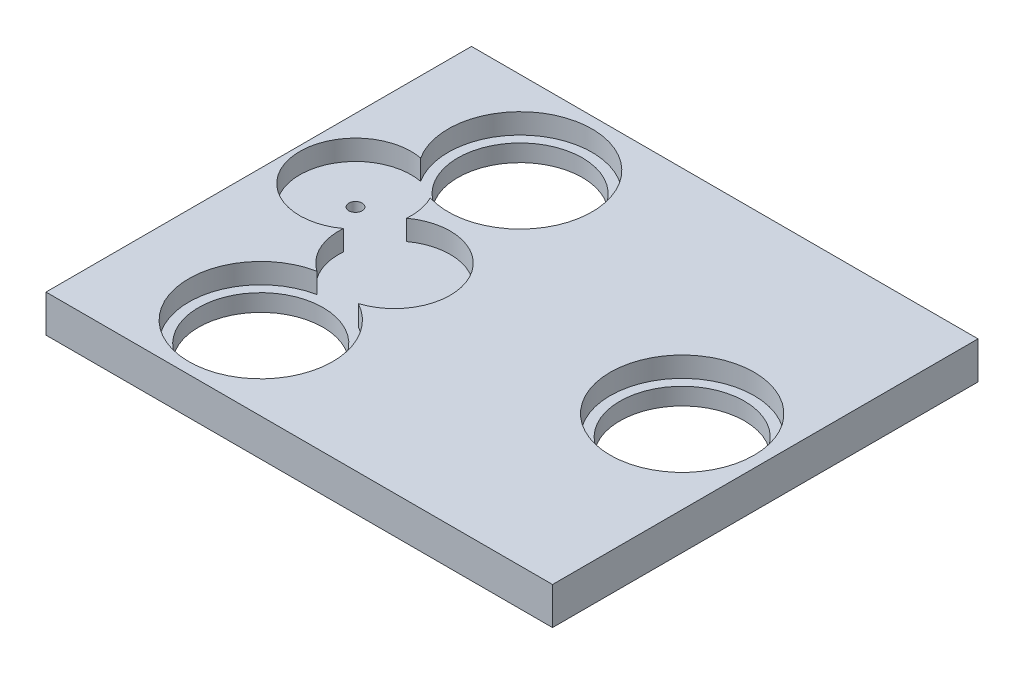
SolidWorks part; units mm, degrees
ref_plane "Front" through (0, 0, 0) normal (0, 0, 1) x (1, 0, 0)
ref_plane "Top" through (0, 0, 0) normal (0, 1, 0) x (1, 0, 0)
ref_plane "Right" through (0, 0, 0) normal (1, 0, 0) x (0, 0, -1)
sketch "Sketch1" plane through (0, 0, 0) normal (0, 1, 0) x (1, 0, 0)
  line L1 (-62.5, -52.5) -> (62.5, -52.5)
  line L2 (-62.5, -52.5) -> (-62.5, 52.5)
  line L3 (-62.5, 52.5) -> (62.5, 52.5)
  line L4 (62.5, -52.5) -> (62.5, 52.5)
  line L5 (-62.5, -52.5) -> (62.5, 52.5) construction
  line L6 (-62.5, 52.5) -> (62.5, -52.5) construction
  point P0 (0, 0)
  dimension "D1" = 125
  dimension "D2" = 105
extrude "Test_Base_Postion" add sketch "Sketch1" along normal blind 9.215
sketch "Thumb_Position" plane through (0, 9.215, 0) normal (0, 1, 0) x (1, 0, 0)
  line L0 (62.5, -52.5) -> (62.5, 52.5) construction
  line L1 (49, -12) -> (17, -12)
  line L2 (49, -12) -> (49, 43)
  line L3 (49, 43) -> (17, 43)
  line L4 (17, -12) -> (17, 43)
  line L5 (33, 43) -> (33, -12) construction
  line L6 (51, -12) -> (15, -12)
  line L7 (51, -12) -> (51, 12)
  line L8 (51, 12) -> (15, 12)
  line L9 (15, -12) -> (15, 12)
  line L10 (33, 12) -> (33, -12) construction
  line L12 (51, 0) -> (15, 0) construction
  circle A1 centre (42, 0) radius 9
  circle A2 centre (42, 0) radius 17.75 construction
  dimension "D6" = 18
  dimension "D7" = 20.5
  dimension "D5" = 35.5
  dimension "D1" = 55
  dimension "D2" = 32
  dimension "D3" = 36
  dimension "D4" = 24
sketch "Finger_Gears_Position" plane through (0, 0, 0) normal (0, -1, 0) x (1, 0, 0)
  line L0 (-30, 32) -> (-30, 49.5) construction
  line L1 (-30, 32) -> (-47.5, 32) construction
  line L2 (-30, -32) -> (-30, -49.5) construction
  line L3 (-30, -32) -> (-47.5, -32) construction
  line L4 (-62.5, -52.5) -> (-62.5, 52.5) construction
  line L5 (-62.5, 52.5) -> (62.5, 52.5) construction
  line L8 (62.5, -52.5) -> (-62.5, -52.5) construction
  line L9 (-62.5, 0) -> (62.5, 0) construction
  line L10 (62.5, 52.5) -> (62.5, -52.5) construction
  line L13 (-30, -32) -> (-43, -32) construction
  line L15 (-43, -48) -> (12, -48) construction
  line L16 (-43, -48) -> (-43, -16) construction
  line L17 (-43, -16) -> (12, -16) construction
  line L18 (12, -48) -> (12, -16) construction
  line L20 (-30, 32) -> (-43, 32) construction
  line L21 (12, -32) -> (-23, -32) construction
  line L22 (-43, 16) -> (12, 16) construction
  line L23 (-43, 16) -> (-43, 48) construction
  line L24 (-43, 48) -> (12, 48) construction
  line L25 (12, 16) -> (12, 48) construction
  line L26 (12, 32) -> (-23, 32) construction
  line L27 (-23, -32) -> (-23, 32) construction
  circle A0 centre (-30, 32) radius 17.5 construction
  circle A1 centre (-30, -32) radius 17.5 construction
  dimension "D1" = 35
  dimension "D2" = 15
  dimension "D3" = 3
  dimension "D4" = 3
  dimension "D5" = 13
  dimension "D6" = 55
  dimension "D7" = 32
  dimension "D8" = 13
  dimension "D9" = 55
  dimension "D10" = 32
  dimension "D11" = 35
  dimension "D12" = 35
sketch "Fingers_Position" plane through (0, 9.215, 0) normal (0, 1, 0) x (1, 0, 0)
  line L0 (12, 32) -> (-23, 32) construction
  line L1 (12, 16) -> (-43, 16)
  line L2 (12, 16) -> (12, 48)
  line L3 (12, 48) -> (-43, 48)
  line L4 (-43, 16) -> (-43, 48)
  line L5 (12, -48) -> (-43, -48)
  line L6 (12, -48) -> (12, -16)
  line L7 (12, -16) -> (-43, -16)
  line L8 (-43, -48) -> (-43, -16)
  line L9 (-23, 32) -> (-23, -32) construction
  line L10 (-23, -32) -> (12, -32) construction
sketch "Thumb_Knuckle_Mount_Position" plane through (0, 0, 0) normal (0, -1, 0) x (1, 0, 0)
  circle A0 centre (42, 0) radius 17.75
  dimension "D1" = 35.5
sketch "Gears_Position" plane through (0, 0, 0) normal (0, -1, 0) x (-1, 0, 0)
  line L0 (30, 32) -> (30, 13.5) construction
  line L1 (30, 32) -> (30.5905, 16.5113) construction
  line L2 (30.7851, 15.5187) -> (29.2149, 15.5187) construction
  line L3 (31.4977, 13.5607) -> (30, 17.6757) construction
  line L4 (28.2415, 13.5838) -> (30, 32) construction
  line L5 (29.2149, 15.5187) -> (27.6518, 15.6679) construction
  line L6 (30, -32) -> (30, -50.5) construction
  line L7 (30.7851, -48.4813) -> (29.2149, -48.4813) construction
  line L8 (30.5905, -47.4887) -> (30, -32) construction
  line L9 (31.4977, -50.4393) -> (30, -46.3243) construction
  line L10 (30, -32) -> (28.2415, -50.4162) construction
  line L11 (29.2149, -48.4813) -> (27.6518, -48.3321) construction
  line L12 (47.5, 8.8753) -> (47.5, -5.6247) construction
  line L13 (47.5, 8.8753) -> (48.0842, -2.6098) construction
  line L14 (48.2849, -3.6) -> (46.7151, -3.6) construction
  line L15 (48.9937, -5.5475) -> (47.5, -1.4436) construction
  line L16 (47.5, 8.8753) -> (45.6827, -5.5103) construction
  line L17 (46.7151, -3.6) -> (45.1577, -3.4033) construction
  line L18 (26.4633, -15.7991) -> (24.8935, -15.7991) construction
  line L19 (25.6784, -3.3238) -> (23.8611, -17.7095) construction
  line L20 (24.8935, -15.7991) -> (23.3362, -15.6024) construction
  line L21 (25.6784, -3.3238) -> (25.6784, -17.8238) construction
  line L22 (25.6784, -3.3238) -> (26.2626, -14.809) construction
  line L23 (27.1722, -17.7467) -> (25.6784, -13.6427) construction
  line L24 (-0.062, 11.1823) -> (33.5, -16.1231) construction
  line L25 (35.7758, 7.7687) -> (-2.3378, -12.7095) construction
  line L26 (-0.062, 11.1823) -> (35.7758, 7.7687) construction
  line L27 (-0.062, 11.1823) -> (-2.3378, -12.7095) construction
  line L28 (-2.3378, -12.7095) -> (33.5, -16.1231) construction
  line L29 (35.7758, 7.7687) -> (33.5, -16.1231) construction
  line L30 (16.719, -2.4704) -> (34.6379, -4.1772) construction
  line L31 (62.5, 52.5) -> (62.5, -52.5) construction
  circle A0 centre (30, -32) radius 17.5 construction
  circle A1 centre (30, 32) radius 17.5 construction
  circle A2 centre (30, 32) radius 16.5
  circle A3 centre (30, 32) radius 15.5 construction
  circle A4 centre (30, 32) radius 18.5 construction
  arc A5 (32.4899, 13.6683) -> (30.5905, 16.5113) centre (33.854, 16.6357) cw
  arc A6 (27.5101, 13.6683) -> (29.4095, 16.5113) centre (26.146, 16.6357) ccw
  arc A7 (32.4899, -50.3317) -> (30.5905, -47.4887) centre (33.854, -47.3643) cw
  arc A8 (27.5101, -50.3317) -> (29.4095, -47.4887) centre (26.146, -47.3643) ccw
  circle A9 centre (30, -32) radius 16.5
  circle A10 centre (30, -32) radius 18.5 construction
  circle A11 centre (30, -32) radius 15.5 construction
  arc A12 (28.9757, -50.4716) -> (27.6486, -47.3206) centre (30.8766, -47.816) cw
  arc A13 (24.0858, -49.5292) -> (26.4889, -47.0971) centre (23.3079, -46.3573) ccw
  arc A14 (25.4984, -49.944) -> (24.7916, -46.5987) centre (27.8676, -47.6961) cw
  arc A15 (20.8752, -48.0931) -> (23.6952, -46.1598) centre (20.7117, -44.8314) ccw
  arc A16 (22.1838, -48.7678) -> (22.1229, -45.3492) centre (24.9356, -47.0089) cw
  arc A17 (17.9945, -46.0754) -> (21.1294, -44.7107) centre (18.4512, -42.8417) ccw
  arc A18 (19.1518, -46.9855) -> (19.7389, -43.6172) centre (22.1867, -45.7792) cw
  arc A19 (15.5476, -43.549) -> (18.8842, -42.8022) centre (16.6081, -40.4601) ccw
  arc A20 (16.5118, -44.6617) -> (17.7258, -41.4654) centre (19.7201, -44.0516) cw
  arc A21 (13.6232, -40.6052) -> (17.0407, -40.5033) centre (15.2491, -37.7728) ccw
  arc A22 (14.3593, -41.8802) -> (16.1562, -38.9714) centre (17.6251, -41.8883) cw
  arc A23 (12.2906, -37.3503) -> (15.6656, -37.8971) centre (14.4231, -34.8769) ccw
  arc A24 (12.7721, -38.7416) -> (15.0871, -36.2255) centre (15.9774, -39.3676) cw
  arc A25 (11.598, -33.9021) -> (14.8086, -35.0777) centre (14.1602, -31.8769) ccw
  arc A26 (11.8076, -35.3594) -> (14.5569, -33.3268) centre (14.8365, -36.5807) cw
  arc A27 (11.5706, -30.3851) -> (14.5007, -32.1471) centre (14.4697, -28.8814) ccw
  arc A28 (11.5006, -31.8557) -> (14.5849, -30.3802) centre (14.2436, -33.6282) cw
  arc A29 (12.2093, -26.9265) -> (14.7529, -29.2112) centre (15.3405, -25.9987) ccw
  arc A30 (11.8622, -28.3573) -> (15.17, -27.4922) centre (14.2202, -30.6169) cw
  arc A31 (13.4909, -23.6513) -> (15.5563, -26.3761) centre (16.7412, -23.3328) ccw
  arc A32 (12.8793, -24.9905) -> (16.2911, -24.767) centre (14.7671, -27.6555) cw
  arc A33 (15.3693, -20.6778) -> (16.8816, -23.7442) centre (18.6211, -20.9802) ccw
  arc A34 (14.5153, -21.8771) -> (17.9077, -22.3033) centre (15.8646, -24.8512) cw
  arc A35 (17.7764, -18.1135) -> (18.6811, -21.4107) centre (20.9122, -19.0259) ccw
  arc A36 (16.7109, -19.1295) -> (19.9613, -20.1901) centre (17.473, -22.3052) cw
  arc A37 (20.6253, -16.0511) -> (20.8897, -19.46) centre (23.5318, -17.5404) ccw
  arc A38 (19.3868, -16.8471) -> (22.3778, -18.5036) centre (19.5341, -20.1096) cw
  arc A39 (23.8131, -14.5652) -> (23.4275, -17.9625) centre (26.3852, -16.5776) ccw
  arc A40 (22.4463, -15.1124) -> (25.0697, -17.305) centre (21.9735, -18.3438) cw
  arc A41 (27.2245, -13.7094) -> (26.2029, -16.9723) centre (29.3693, -16.1722) ccw
  arc A42 (25.7788, -13.988) -> (27.9399, -16.6375) centre (24.703, -17.0716) cw
  arc A43 (30.7361, -13.5147) -> (29.1155, -16.5253) centre (32.3761, -16.3389) ccw
  arc A44 (29.2639, -13.5147) -> (30.8845, -16.5253) centre (27.6239, -16.3389) cw
  arc A45 (34.2212, -13.988) -> (32.0601, -16.6375) centre (35.297, -17.0716) ccw
  arc A46 (32.7755, -13.7094) -> (33.7971, -16.9723) centre (30.6307, -16.1722) cw
  arc A47 (37.5537, -15.1124) -> (34.9303, -17.305) centre (38.0265, -18.3438) ccw
  arc A48 (36.1869, -14.5652) -> (36.5725, -17.9625) centre (33.6148, -16.5776) cw
  arc A49 (40.6132, -16.8471) -> (37.6222, -18.5036) centre (40.4659, -20.1096) ccw
  arc A50 (39.3747, -16.0511) -> (39.1103, -19.46) centre (36.4682, -17.5404) cw
  arc A51 (43.2891, -19.1295) -> (40.0387, -20.1901) centre (42.527, -22.3052) ccw
  arc A52 (42.2236, -18.1135) -> (41.3189, -21.4107) centre (39.0878, -19.0259) cw
  arc A53 (45.4847, -21.8771) -> (42.0923, -22.3033) centre (44.1354, -24.8512) ccw
  arc A54 (44.6307, -20.6778) -> (43.1184, -23.7442) centre (41.3789, -20.9802) cw
  arc A55 (47.1207, -24.9905) -> (43.7089, -24.767) centre (45.2329, -27.6555) ccw
  arc A56 (46.5091, -23.6513) -> (44.4437, -26.3761) centre (43.2588, -23.3328) cw
  arc A57 (48.1378, -28.3573) -> (44.83, -27.4922) centre (45.7798, -30.6169) ccw
  arc A58 (47.7907, -26.9265) -> (45.2471, -29.2112) centre (44.6595, -25.9987) cw
  arc A59 (48.4994, -31.8557) -> (45.4151, -30.3802) centre (45.7564, -33.6282) ccw
  arc A60 (48.4294, -30.3851) -> (45.4993, -32.1471) centre (45.5303, -28.8814) cw
  arc A61 (48.1924, -35.3594) -> (45.4431, -33.3268) centre (45.1635, -36.5807) ccw
  arc A62 (48.402, -33.9021) -> (45.1914, -35.0777) centre (45.8398, -31.8769) cw
  arc A63 (47.2279, -38.7416) -> (44.9129, -36.2255) centre (44.0226, -39.3676) ccw
  arc A64 (47.7094, -37.3503) -> (44.3344, -37.8971) centre (45.5769, -34.8769) cw
  arc A65 (45.6407, -41.8802) -> (43.8438, -38.9714) centre (42.3749, -41.8883) ccw
  arc A66 (46.3768, -40.6052) -> (42.9593, -40.5033) centre (44.7509, -37.7728) cw
  arc A67 (43.4882, -44.6617) -> (42.2742, -41.4654) centre (40.2799, -44.0516) ccw
  arc A68 (44.4524, -43.549) -> (41.1158, -42.8022) centre (43.3919, -40.4601) cw
  arc A69 (40.8482, -46.9855) -> (40.2611, -43.6172) centre (37.8133, -45.7792) ccw
  arc A70 (42.0055, -46.0754) -> (38.8706, -44.7107) centre (41.5488, -42.8417) cw
  arc A71 (37.8162, -48.7678) -> (37.8771, -45.3492) centre (35.0644, -47.0089) ccw
  arc A72 (39.1248, -48.0931) -> (36.3048, -46.1598) centre (39.2883, -44.8314) cw
  arc A73 (34.5016, -49.944) -> (35.2084, -46.5987) centre (32.1324, -47.6961) ccw
  arc A74 (35.9142, -49.5292) -> (33.5111, -47.0971) centre (36.6921, -46.3573) cw
  arc A75 (31.0243, -50.4716) -> (32.3514, -47.3206) centre (29.1234, -47.816) ccw
  arc A76 (28.9757, 13.5284) -> (27.6486, 16.6794) centre (30.8766, 16.184) cw
  arc A77 (24.0858, 14.4708) -> (26.4889, 16.9029) centre (23.3079, 17.6427) ccw
  arc A78 (25.4984, 14.056) -> (24.7916, 17.4013) centre (27.8676, 16.3039) cw
  arc A79 (20.8752, 15.9069) -> (23.6952, 17.8402) centre (20.7117, 19.1686) ccw
  arc A80 (22.1838, 15.2322) -> (22.1229, 18.6508) centre (24.9356, 16.9911) cw
  arc A81 (17.9945, 17.9246) -> (21.1294, 19.2893) centre (18.4512, 21.1583) ccw
  arc A82 (19.1518, 17.0145) -> (19.7389, 20.3828) centre (22.1867, 18.2208) cw
  arc A83 (15.5476, 20.451) -> (18.8842, 21.1978) centre (16.6081, 23.5399) ccw
  arc A84 (16.5118, 19.3383) -> (17.7258, 22.5346) centre (19.7201, 19.9484) cw
  arc A85 (13.6232, 23.3948) -> (17.0407, 23.4967) centre (15.2491, 26.2272) ccw
  arc A86 (14.3593, 22.1198) -> (16.1562, 25.0286) centre (17.6251, 22.1117) cw
  arc A87 (12.2906, 26.6497) -> (15.6656, 26.1029) centre (14.4231, 29.1231) ccw
  arc A88 (12.7721, 25.2584) -> (15.0871, 27.7745) centre (15.9774, 24.6324) cw
  arc A89 (11.598, 30.0979) -> (14.8086, 28.9223) centre (14.1602, 32.1231) ccw
  arc A90 (11.8076, 28.6406) -> (14.5569, 30.6732) centre (14.8365, 27.4193) cw
  arc A91 (11.5706, 33.6149) -> (14.5007, 31.8529) centre (14.4697, 35.1186) ccw
  arc A92 (11.5006, 32.1443) -> (14.5849, 33.6198) centre (14.2436, 30.3718) cw
  arc A93 (12.2093, 37.0735) -> (14.7529, 34.7888) centre (15.3405, 38.0013) ccw
  arc A94 (11.8622, 35.6427) -> (15.17, 36.5078) centre (14.2202, 33.3831) cw
  arc A95 (13.4909, 40.3487) -> (15.5563, 37.6239) centre (16.7412, 40.6672) ccw
  arc A96 (12.8793, 39.0095) -> (16.2911, 39.233) centre (14.7671, 36.3445) cw
  arc A97 (15.3693, 43.3222) -> (16.8816, 40.2558) centre (18.6211, 43.0198) ccw
  arc A98 (14.5153, 42.1229) -> (17.9077, 41.6967) centre (15.8646, 39.1488) cw
  arc A99 (17.7764, 45.8865) -> (18.6811, 42.5893) centre (20.9122, 44.9741) ccw
  arc A100 (16.7109, 44.8705) -> (19.9613, 43.8099) centre (17.473, 41.6948) cw
  arc A101 (20.6253, 47.9489) -> (20.8897, 44.54) centre (23.5318, 46.4596) ccw
  arc A102 (19.3868, 47.1529) -> (22.3778, 45.4964) centre (19.5341, 43.8904) cw
  arc A103 (23.8131, 49.4348) -> (23.4275, 46.0375) centre (26.3852, 47.4224) ccw
  arc A104 (22.4463, 48.8876) -> (25.0697, 46.695) centre (21.9735, 45.6562) cw
  arc A105 (27.2245, 50.2906) -> (26.2029, 47.0277) centre (29.3693, 47.8278) ccw
  arc A106 (25.7788, 50.012) -> (27.9399, 47.3625) centre (24.703, 46.9284) cw
  arc A107 (30.7361, 50.4853) -> (29.1155, 47.4747) centre (32.3761, 47.6611) ccw
  arc A108 (29.2639, 50.4853) -> (30.8845, 47.4747) centre (27.6239, 47.6611) cw
  arc A109 (34.2212, 50.012) -> (32.0601, 47.3625) centre (35.297, 46.9284) ccw
  arc A110 (32.7755, 50.2906) -> (33.7971, 47.0277) centre (30.6307, 47.8278) cw
  arc A111 (37.5537, 48.8876) -> (34.9303, 46.695) centre (38.0265, 45.6562) ccw
  arc A112 (36.1869, 49.4348) -> (36.5725, 46.0375) centre (33.6148, 47.4224) cw
  arc A113 (40.6132, 47.1529) -> (37.6222, 45.4964) centre (40.4659, 43.8904) ccw
  arc A114 (39.3747, 47.9489) -> (39.1103, 44.54) centre (36.4682, 46.4596) cw
  arc A115 (43.2891, 44.8705) -> (40.0387, 43.8099) centre (42.527, 41.6948) ccw
  arc A116 (42.2236, 45.8865) -> (41.3189, 42.5893) centre (39.0878, 44.9741) cw
  arc A117 (45.4847, 42.1229) -> (42.0923, 41.6967) centre (44.1354, 39.1488) ccw
  arc A118 (44.6307, 43.3222) -> (43.1184, 40.2558) centre (41.3789, 43.0198) cw
  arc A119 (47.1207, 39.0095) -> (43.7089, 39.233) centre (45.2329, 36.3445) ccw
  arc A120 (46.5091, 40.3487) -> (44.4437, 37.6239) centre (43.2588, 40.6672) cw
  arc A121 (48.1378, 35.6427) -> (44.83, 36.5078) centre (45.7798, 33.3831) ccw
  arc A122 (47.7907, 37.0735) -> (45.2471, 34.7888) centre (44.6595, 38.0013) cw
  arc A123 (48.4994, 32.1443) -> (45.4151, 33.6198) centre (45.7564, 30.3718) ccw
  arc A124 (48.4294, 33.6149) -> (45.4993, 31.8529) centre (45.5303, 35.1186) cw
  arc A125 (48.1924, 28.6406) -> (45.4431, 30.6732) centre (45.1635, 27.4193) ccw
  arc A126 (48.402, 30.0979) -> (45.1914, 28.9223) centre (45.8398, 32.1231) cw
  arc A127 (47.2279, 25.2584) -> (44.9129, 27.7745) centre (44.0226, 24.6324) ccw
  arc A128 (47.7094, 26.6497) -> (44.3344, 26.1029) centre (45.5769, 29.1231) cw
  arc A129 (45.6407, 22.1198) -> (43.8438, 25.0286) centre (42.3749, 22.1117) ccw
  arc A130 (46.3768, 23.3948) -> (42.9593, 23.4967) centre (44.7509, 26.2272) cw
  arc A131 (43.4882, 19.3383) -> (42.2742, 22.5346) centre (40.2799, 19.9484) ccw
  arc A132 (44.4524, 20.451) -> (41.1158, 21.1978) centre (43.3919, 23.5399) cw
  arc A133 (40.8482, 17.0145) -> (40.2611, 20.3828) centre (37.8133, 18.2208) ccw
  arc A134 (42.0055, 17.9246) -> (38.8706, 19.2893) centre (41.5488, 21.1583) cw
  arc A135 (37.8162, 15.2322) -> (37.8771, 18.6508) centre (35.0644, 16.9911) ccw
  arc A136 (39.1248, 15.9069) -> (36.3048, 17.8402) centre (39.2883, 19.1686) cw
  arc A137 (34.5016, 14.056) -> (35.2084, 17.4013) centre (32.1324, 16.3039) ccw
  arc A138 (35.9142, 14.4708) -> (33.5111, 16.9029) centre (36.6921, 17.6427) cw
  arc A139 (31.0243, 13.5284) -> (32.3514, 16.6794) centre (29.1234, 16.184) ccw
  circle A140 centre (47.5, 8.8753) radius 11.5 construction
  circle A141 centre (47.5, 8.8753) radius 12.5
  circle A142 centre (47.5, 8.8753) radius 13.5 construction
  circle A143 centre (47.5, 8.8753) radius 14.5 construction
  arc A144 (49.8668, -5.4302) -> (48.0842, -2.6098) centre (51.48, -2.4371) cw
  arc A145 (45.1332, -5.4302) -> (46.9158, -2.6098) centre (43.52, -2.4371) ccw
  arc A146 (23.3116, -17.6293) -> (25.0942, -14.809) centre (21.6985, -14.6362) ccw
  circle A147 centre (25.6784, -3.3238) radius 11.5 construction
  circle A148 centre (25.6784, -3.3238) radius 12.5
  arc A149 (28.0453, -17.6293) -> (26.2626, -14.809) centre (29.6584, -14.6362) cw
  circle A150 centre (25.6784, -3.3238) radius 13.5 construction
  circle A151 centre (25.6784, -3.3238) radius 14.5 construction
  arc A152 (46.2348, -5.5694) -> (45.2096, -2.3943) centre (48.5416, -3.0715) cw
  arc A153 (41.6499, -4.3922) -> (44.0779, -2.1037) centre (40.8318, -1.0919) ccw
  arc A154 (42.6823, -4.8009) -> (42.4789, -1.4706) centre (45.5379, -2.9552) cw
  arc A155 (38.5342, -2.5205) -> (41.455, -0.9077) centre (38.5625, 0.8796) ccw
  arc A156 (39.4325, -3.1731) -> (40.0638, 0.1031) centre (42.6574, -2.0955) cw
  arc A157 (35.9819, 0.0673) -> (39.212, 0.9029) centre (36.8548, 3.3534) ccw
  arc A158 (36.6896, -0.7883) -> (38.1158, 2.228) centre (40.0812, -0.5466) cw
  arc A159 (34.1532, 3.2084) -> (37.4897, 3.2146) centre (35.816, 6.1742) ccw
  arc A160 (34.626, 2.2037) -> (36.7575, 4.7706) centre (37.9711, 1.5944) cw
  arc A161 (33.1632, 6.7057) -> (36.3964, 5.8819) centre (35.5114, 9.1648) ccw
  arc A162 (33.3713, 5.6149) -> (36.0742, 7.5711) centre (36.4598, 4.1929) cw
  arc A163 (33.0741, 10.3392) -> (36.0008, 8.7372) centre (35.96, 12.1371) ccw
  arc A164 (33.0044, 9.231) -> (36.1088, 10.4536) centre (35.6422, 7.0856) cw
  arc A165 (33.8914, 13.8808) -> (36.3278, 11.6013) centre (37.1337, 14.9045) ccw
  arc A166 (33.5482, 12.8248) -> (36.8592, 13.2369) centre (35.5696, 10.0908) cw
  arc A167 (35.5637, 17.1079) -> (37.3567, 14.2941) centre (38.9588, 17.2931) ccw
  arc A168 (34.9687, 16.1704) -> (38.2781, 15.7461) centre (36.2467, 13.0195) cw
  arc A169 (37.9861, 19.8177) -> (39.0229, 16.6464) centre (41.3206, 19.1528) ccw
  arc A170 (37.1766, 19.0576) -> (40.2766, 17.8236) centre (37.6309, 15.6879) cw
  arc A171 (41.0062, 21.8399) -> (41.2218, 18.5104) centre (44.0706, 20.3666) ccw
  arc A172 (40.0332, 21.305) -> (42.7288, 19.3389) centre (39.6351, 17.9282) cw
  arc A173 (44.4344, 23.0476) -> (43.8152, 19.769) centre (47.0361, 20.8585) ccw
  arc A174 (43.3589, 22.7714) -> (45.4809, 20.1967) centre (42.1336, 19.5997) cw
  arc A175 (48.0552, 23.3647) -> (46.6401, 20.3431) centre (50.0308, 20.5974) ccw
  arc A176 (46.9448, 23.3647) -> (48.3599, 20.3431) centre (44.9692, 20.5974) cw
  arc A177 (51.6411, 22.7714) -> (49.5191, 20.1967) centre (52.8664, 19.5997) ccw
  arc A178 (50.5656, 23.0476) -> (51.1848, 19.769) centre (47.9639, 20.8585) cw
  arc A179 (54.9668, 21.305) -> (52.2712, 19.3389) centre (55.3649, 17.9282) ccw
  arc A180 (53.9938, 21.8399) -> (53.7782, 18.5104) centre (50.9294, 20.3666) cw
  arc A181 (57.8234, 19.0576) -> (54.7234, 17.8236) centre (57.3691, 15.6879) ccw
  arc A182 (57.0139, 19.8177) -> (55.9771, 16.6464) centre (53.6794, 19.1528) cw
  arc A183 (60.0313, 16.1704) -> (56.7219, 15.7461) centre (58.7533, 13.0195) ccw
  arc A184 (59.4363, 17.1079) -> (57.6433, 14.2941) centre (56.0412, 17.2931) cw
  arc A185 (61.4518, 12.8248) -> (58.1408, 13.2369) centre (59.4304, 10.0908) ccw
  arc A186 (61.1086, 13.8808) -> (58.6722, 11.6013) centre (57.8663, 14.9045) cw
  arc A187 (61.9956, 9.231) -> (58.8912, 10.4536) centre (59.3578, 7.0856) ccw
  arc A188 (61.9259, 10.3392) -> (58.9992, 8.7372) centre (59.04, 12.1371) cw
  arc A189 (61.6287, 5.6149) -> (58.9258, 7.5711) centre (58.5402, 4.1929) ccw
  arc A190 (61.8368, 6.7057) -> (58.6036, 5.8819) centre (59.4886, 9.1648) cw
  arc A191 (60.374, 2.2037) -> (58.2425, 4.7706) centre (57.0289, 1.5944) ccw
  arc A192 (60.8468, 3.2084) -> (57.5103, 3.2146) centre (59.184, 6.1742) cw
  arc A193 (58.3104, -0.7883) -> (56.8842, 2.228) centre (54.9188, -0.5466) ccw
  arc A194 (59.0181, 0.0673) -> (55.788, 0.9029) centre (58.1452, 3.3534) cw
  arc A195 (55.5675, -3.1731) -> (54.9362, 0.1031) centre (52.3426, -2.0955) ccw
  arc A196 (56.4658, -2.5205) -> (53.545, -0.9077) centre (56.4375, 0.8796) cw
  arc A197 (52.3177, -4.8009) -> (52.5211, -1.4706) centre (49.4621, -2.9552) ccw
  arc A198 (53.3501, -4.3922) -> (50.9221, -2.1037) centre (54.1682, -1.0919) cw
  arc A199 (48.7652, -5.5694) -> (49.7904, -2.3943) centre (46.4584, -3.0715) ccw
  arc A200 (19.8283, -16.5913) -> (22.2563, -14.3028) centre (19.0102, -13.291) ccw
  arc A201 (24.4133, -17.7685) -> (23.3881, -14.5934) centre (26.7201, -15.2706) cw
  arc A202 (16.7126, -14.7196) -> (19.6335, -13.1069) centre (16.741, -11.3196) ccw
  arc A203 (20.8608, -17.0001) -> (20.6574, -13.6698) centre (23.7163, -15.1543) cw
  arc A204 (14.1603, -12.1319) -> (17.3904, -11.2962) centre (15.0333, -8.8457) ccw
  arc A205 (17.611, -15.3723) -> (18.2422, -12.096) centre (20.8358, -14.2947) cw
  arc A206 (12.3317, -8.9907) -> (15.6682, -8.9846) centre (13.9945, -6.0249) ccw
  arc A207 (14.8681, -12.9875) -> (16.2942, -9.9711) centre (18.2596, -12.7457) cw
  arc A208 (11.3417, -5.4935) -> (14.5749, -6.3173) centre (13.6898, -3.0344) ccw
  arc A209 (12.8045, -9.9954) -> (14.9359, -7.4285) centre (16.1496, -10.6047) cw
  arc A210 (11.2525, -1.8599) -> (14.1793, -3.4619) centre (14.1384, -0.062) ccw
  arc A211 (11.5497, -6.5842) -> (14.2526, -4.628) centre (14.6382, -8.0062) cw
  arc A212 (12.0698, 1.6817) -> (14.5062, -0.5978) centre (15.3122, 2.7054) ccw
  arc A213 (11.1828, -2.9681) -> (14.2872, -1.7456) centre (13.8206, -5.1135) cw
  arc A214 (13.7421, 4.9088) -> (15.5351, 2.0949) centre (17.1372, 5.094) ccw
  arc A215 (11.7267, 0.6256) -> (15.0376, 1.0377) centre (13.7481, -2.1084) cw
  arc A216 (16.1645, 7.6185) -> (17.2014, 4.4473) centre (19.499, 6.9536) ccw
  arc A217 (13.1472, 3.9712) -> (16.4566, 3.547) centre (14.4251, 0.8204) cw
  arc A218 (19.1847, 9.6408) -> (19.4003, 6.3113) centre (22.249, 8.1675) ccw
  arc A219 (15.3551, 6.8584) -> (18.455, 5.6245) centre (15.8093, 3.4888) cw
  arc A220 (22.6128, 10.8484) -> (21.9937, 7.5699) centre (25.2145, 8.6593) ccw
  arc A221 (18.2116, 9.1059) -> (20.9073, 7.1398) centre (17.8136, 5.7291) cw
  arc A222 (26.2336, 11.1656) -> (24.8186, 8.144) centre (28.2092, 8.3982) ccw
  arc A223 (21.5373, 10.5723) -> (23.6593, 7.9976) centre (20.312, 7.4006) cw
  arc A224 (29.8195, 10.5723) -> (27.6975, 7.9976) centre (31.0448, 7.4006) ccw
  arc A225 (25.1232, 11.1656) -> (26.5383, 8.144) centre (23.1477, 8.3982) cw
  arc A226 (33.1453, 9.1059) -> (30.4496, 7.1398) centre (33.5433, 5.7291) ccw
  arc A227 (28.744, 10.8484) -> (29.3632, 7.5699) centre (26.1423, 8.6593) cw
  arc A228 (36.0018, 6.8584) -> (32.9019, 5.6245) centre (35.5476, 3.4888) ccw
  arc A229 (32.1722, 9.6408) -> (31.9566, 6.3113) centre (29.1078, 8.1675) cw
  arc A230 (38.2097, 3.9712) -> (34.9003, 3.547) centre (36.9317, 0.8204) ccw
  arc A231 (35.1924, 7.6185) -> (34.1555, 4.4473) centre (31.8579, 6.9536) cw
  arc A232 (39.6302, 0.6256) -> (36.3193, 1.0377) centre (37.6088, -2.1084) ccw
  arc A233 (37.6147, 4.9088) -> (35.8218, 2.0949) centre (34.2196, 5.094) cw
  arc A234 (40.1741, -2.9681) -> (37.0696, -1.7456) centre (37.5362, -5.1135) ccw
  arc A235 (39.2871, 1.6817) -> (36.8507, -0.5978) centre (36.0447, 2.7054) cw
  arc A236 (39.8071, -6.5842) -> (37.1042, -4.628) centre (36.7186, -8.0062) ccw
  arc A237 (40.1043, -1.8599) -> (37.1776, -3.4619) centre (37.2184, -0.062) cw
  arc A238 (38.5524, -9.9954) -> (36.4209, -7.4285) centre (35.2073, -10.6047) ccw
  arc A239 (40.0152, -5.4935) -> (36.782, -6.3173) centre (37.6671, -3.0344) cw
  arc A240 (36.4888, -12.9875) -> (35.0626, -9.9711) centre (33.0972, -12.7457) ccw
  arc A241 (39.0252, -8.9907) -> (35.6887, -8.9846) centre (37.3624, -6.0249) cw
  arc A242 (33.7459, -15.3723) -> (33.1147, -12.096) centre (30.521, -14.2947) ccw
  arc A243 (37.1966, -12.1319) -> (33.9664, -11.2962) centre (36.3236, -8.8457) cw
  arc A244 (30.4961, -17.0001) -> (30.6995, -13.6698) centre (27.6406, -15.1543) ccw
  arc A245 (34.6442, -14.7196) -> (31.7234, -13.1069) centre (34.6159, -11.3196) cw
  arc A246 (26.9436, -17.7685) -> (27.9688, -14.5934) centre (24.6368, -15.2706) ccw
  arc A247 (31.5285, -16.5913) -> (29.1005, -14.3028) centre (32.3466, -13.291) cw
  point P233 (30, -32)
  point P426 (30, 32)
  point P461 (16.719, -2.4704)
  point P607 (47.5, 8.8753)
  point P608 (25.6784, -3.3238)
  point P753 (25.6784, -3.3238)
  dimension "D1" = 35
  dimension "D2" = 31
  dimension "D3" = 33
  dimension "D4" = 37
  dimension "D7" = 37
  dimension "D8" = 33
  dimension "D9" = 31
  dimension "D14" = 23
  dimension "D15" = 25
  dimension "D16" = 27
  dimension "D17" = 29
  dimension "D20" = 23
  dimension "D21" = 25
  dimension "D22" = 27
  dimension "D23" = 29
  dimension "D5" = 20
  dimension "D6" = 5.455
  dimension "D10" = 20
  dimension "D11" = 5.455
  dimension "D18" = 20
  dimension "D19" = 7.2
  dimension "D24" = 20
  dimension "D25" = 7.2
  dimension "D28" = 36
  dimension "D29" = 24
  dimension "D30" = 29
  dimension "D31" = 15
  dimension "D12" = 33
  dimension "D13" = 33
  dimension "D26" = 25
  dimension "D27" = 25
sketch "XL320_Position" plane through (0, 9.215, 0) normal (0, 1, 0) x (1, 0, 0)
  line L0 (0.062, 11.1823) -> (2.3378, -12.7095)
  line L1 (2.3378, -12.7095) -> (-33.5, -16.1231)
  line L2 (-33.5, -16.1231) -> (-35.7758, 7.7687)
  line L3 (-35.7758, 7.7687) -> (0.062, 11.1823)
sketch "Sketch7" plane through (0, 0, 0) normal (0, -1, 0) x (1, 0, 0)
  circle A0 centre (42, 0) radius 17.75
  dimension "D1" = 35.5
extrude "Thumb_Knuckle_Mount" cut sketch "Sketch7" against normal up to surface (5 mm away) from offset 4.215 up to face at (0, 9.215, 0) offset against normal yes
sketch "Sketch8" plane through (0, 0, 0) normal (0, -1, 0) x (1, 0, 0)
  circle A0 centre (42, 0) radius 15.375
  dimension "D1" = 30.75
extrude "Thumb_Knuckle" cut sketch "Sketch8" along direction (0, -1, 0) on the side against the normal up to surface (4.215 mm away)
sketch "Sketch10" plane through (0, 0, 0) normal (0, -1, 0) x (1, 0, 0)
  circle A0 centre (-30, 32) radius 17.75
  circle A1 centre (-25.6784, 3.3238) radius 13.75
  circle A2 centre (-47.5, -8.8753) radius 13.75
  circle A3 centre (-30, -32) radius 17.75
  dimension "D1" = 35.5
  dimension "D2" = 27.5
extrude "Gears_Position_Extrude_Cut" cut sketch "Sketch10" against normal up to surface (5 mm away) from offset 4.215 contours A1 A0 | A2 A1 A0 | A3 A2 A1 | A2 A3 | A0 A1 | A1 A2 | A2 A3 up to face at (42, 9.215, -17.75) offset against normal yes
sketch "Sketch11" plane through (0, 0, 0) normal (0, -1, 0) x (1, 0, 0)
  circle A0 centre (-30, 32) radius 15.375
  circle A1 centre (-30, -32) radius 15.375
  circle A2 centre (-47.5, -8.8753) radius 1.65
  circle A3 centre (-30, 32) radius 17.75 construction
  circle A4 centre (-30, -32) radius 17.75 construction
  circle A5 centre (-47.5, -8.8753) radius 13.75 construction
  dimension "D1" = 3.3
  dimension "D2" = 30.75
extrude "Fingers_Knuckle_Mount_and_Intermediate_Through_Hole" cut sketch "Sketch11" against normal through all
equation "\"D6@Gears_Position\"=180/33"
equation "\"D11@Gears_Position\"=180/33"
equation "\"D19@Gears_Position\"=180/25"
